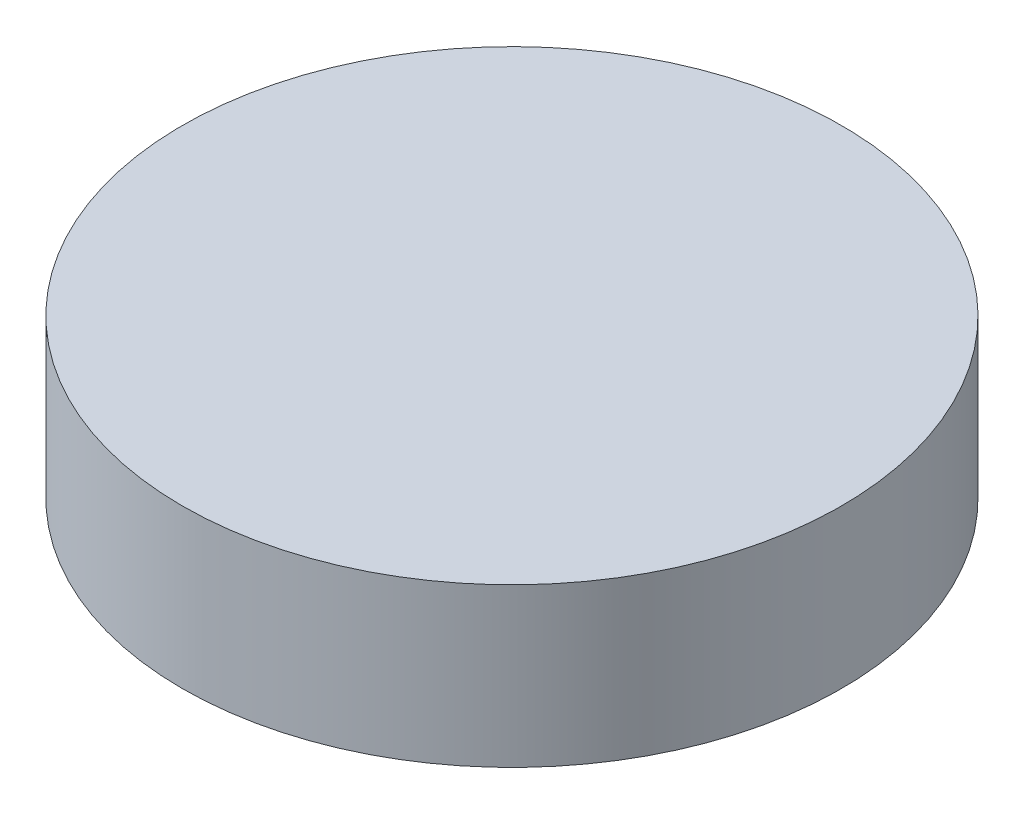
SolidWorks part; units mm, degrees
ref_plane "Front Plane" through (0, 0, 0) normal (0, 0, 1) x (1, 0, 0)
ref_plane "Top Plane" through (0, 0, 0) normal (0, 1, 0) x (1, 0, 0)
ref_plane "Right Plane" through (0, 0, 0) normal (1, 0, 0) x (0, 0, -1)
other "Configuration Table"
sketch "Sketch1" plane through (0, 0, 0) normal (0, 1, 0) x (1, 0, 0)
  circle A0 centre (650, 770) radius 25
extrude "PACK_ayar_ayagi_4" add sketch "Sketch1" along normal blind 12 separate body
